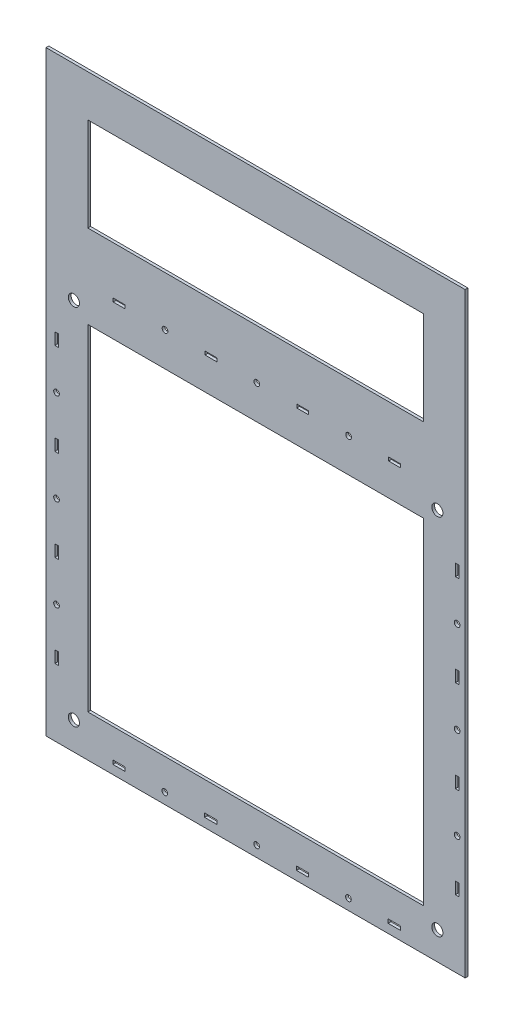
SolidWorks part; units mm, degrees
ref_plane "前视基准面" through (0, 0, 0) normal (0, 0, 1) x (1, 0, 0)
ref_plane "上视基准面" through (0, 0, 0) normal (0, 1, 0) x (1, 0, 0)
ref_plane "右视基准面" through (0, 0, 0) normal (1, 0, 0) x (0, 0, -1)
sketch "草图1" plane through (0, 0, 0) normal (0, 0, 1) x (1, 0, 0)
  line L0 (95.3243, -141.495) -> (104.1243, -141.495)
  line L1 (0.7243, -148.895) -> (0.7243, -142.895) construction
  line L2 (0.7243, -142.895) -> (33.7243, -142.895) construction
  line L3 (33.7243, -142.895) -> (66.7243, -142.895) construction
  line L4 (29.3243, -141.495) -> (38.1243, -141.495)
  line L5 (29.3243, -141.495) -> (29.3243, -144.295)
  line L6 (29.3243, -144.295) -> (38.1243, -144.295)
  line L7 (38.1243, -141.495) -> (38.1243, -144.295)
  line L8 (29.3243, -141.495) -> (38.1243, -144.295) construction
  line L9 (29.3243, -144.295) -> (38.1243, -141.495) construction
  line L10 (66.7243, -142.895) -> (99.7243, -142.895) construction
  line L11 (95.3243, -141.495) -> (95.3243, -144.295)
  line L12 (95.3243, -144.295) -> (104.1243, -144.295)
  line L13 (95.3243, -144.295) -> (104.1243, -141.495) construction
  line L14 (104.1243, -144.295) -> (104.1243, -141.495)
  line L15 (-36.6757, -141.495) -> (-36.6757, -144.295)
  line L16 (-27.8757, -141.495) -> (-36.6757, -141.495)
  line L17 (-27.8757, -141.495) -> (-27.8757, -144.295)
  line L18 (-27.8757, -144.295) -> (-36.6757, -144.295)
  line L19 (-93.8757, -141.495) -> (-93.8757, -144.295)
  line L20 (-102.6757, -144.295) -> (-102.6757, -141.495)
  line L21 (-93.8757, -141.495) -> (-102.6757, -141.495)
  line L22 (-93.8757, -144.295) -> (-102.6757, -144.295)
  line L23 (-141.8757, 95.705) -> (-141.8757, 104.205)
  line L24 (-144.3757, 95.705) -> (-144.3757, 104.205)
  line L25 (-144.3757, 104.205) -> (-141.8757, 104.205)
  line L26 (-141.8757, 95.705) -> (-144.3757, 95.705)
  line L27 (-141.8757, 29.705) -> (-141.8757, 38.205)
  line L28 (-141.8757, 38.205) -> (-144.3757, 38.205)
  line L29 (-144.3757, 29.705) -> (-144.3757, 38.205)
  line L30 (-141.8757, 29.705) -> (-144.3757, 29.705)
  line L31 (-141.8757, -27.795) -> (-144.3757, -27.795)
  line L32 (-141.8757, -27.795) -> (-141.8757, -36.295)
  line L33 (-144.3757, -27.795) -> (-144.3757, -36.295)
  line L34 (-141.8757, -36.295) -> (-144.3757, -36.295)
  line L35 (-141.8757, -93.795) -> (-141.8757, -102.295)
  line L36 (-144.3757, -93.795) -> (-144.3757, -102.295)
  line L37 (-141.8757, -93.795) -> (-144.3757, -93.795)
  line L38 (-144.3757, -102.295) -> (-141.8757, -102.295)
  line L39 (95.6243, 143.705) -> (104.1243, 143.705)
  line L40 (95.6243, 146.205) -> (104.1243, 146.205)
  line L41 (104.1243, 146.205) -> (104.1243, 143.705)
  line L42 (95.6243, 143.705) -> (95.6243, 146.205)
  line L43 (29.6243, 143.705) -> (38.1243, 143.705)
  line L44 (38.1243, 143.705) -> (38.1243, 146.205)
  line L45 (29.6243, 146.205) -> (38.1243, 146.205)
  line L46 (29.6243, 143.705) -> (29.6243, 146.205)
  line L47 (-27.8757, 143.705) -> (-27.8757, 146.205)
  line L48 (-27.8757, 143.705) -> (-36.3757, 143.705)
  line L49 (-27.8757, 146.205) -> (-36.3757, 146.205)
  line L50 (-36.3757, 143.705) -> (-36.3757, 146.205)
  line L51 (-93.8757, 143.705) -> (-102.3757, 143.705)
  line L52 (-93.8757, 146.205) -> (-102.3757, 146.205)
  line L53 (-93.8757, 143.705) -> (-93.8757, 146.205)
  line L54 (-102.3757, 146.205) -> (-102.3757, 143.705)
  line L55 (143.6243, -93.795) -> (143.6243, -102.295)
  line L56 (146.1243, -93.795) -> (146.1243, -102.295)
  line L57 (146.1243, -102.295) -> (143.6243, -102.295)
  line L58 (143.6243, -93.795) -> (146.1243, -93.795)
  line L59 (143.6243, -27.795) -> (143.6243, -36.295)
  line L60 (143.6243, -36.295) -> (146.1243, -36.295)
  line L61 (146.1243, -27.795) -> (146.1243, -36.295)
  line L62 (143.6243, -27.795) -> (146.1243, -27.795)
  line L63 (143.6243, 29.705) -> (146.1243, 29.705)
  line L64 (143.6243, 29.705) -> (143.6243, 38.205)
  line L65 (146.1243, 29.705) -> (146.1243, 38.205)
  line L66 (143.6243, 38.205) -> (146.1243, 38.205)
  line L67 (143.6243, 95.705) -> (143.6243, 104.205)
  line L68 (146.1243, 95.705) -> (146.1243, 104.205)
  line L69 (143.6243, 95.705) -> (146.1243, 95.705)
  line L70 (146.1243, 104.205) -> (143.6243, 104.205)
  line L71 (50.2243, -142.895) -> (50.2243, -127.895) construction
  line L72 (17.2243, -142.895) -> (17.2243, -127.895) construction
  line L73 (120.6507, 120.6507) -> (-120.6507, 120.6507)
  line L74 (150.6507, -150.6507) -> (-150.6507, -150.6507)
  line L75 (99.7243, -142.895) -> (104.1243, -144.295) construction
  line L76 (150.6507, -150.6507) -> (150.6507, 150.6507)
  line L78 (-150.6507, -150.6507) -> (-150.6507, 150.6507)
  line L79 (150.6507, -150.6507) -> (-150.6507, 150.6507) construction
  line L80 (150.6507, 150.6507) -> (-150.6507, -150.6507) construction
  line L81 (-120.6507, -120.6507) -> (-120.6507, 120.6507)
  line L82 (120.6507, -120.6507) -> (-120.6507, -120.6507)
  line L83 (120.6507, -120.6507) -> (120.6507, 120.6507)
  line L84 (-150.6507, 150.6507) -> (-150.6507, 277.9507)
  line L85 (-150.6507, 277.9507) -> (150.6507, 277.9507)
  line L86 (150.6507, 277.9507) -> (150.6507, 150.6507)
  line L87 (150.6507, 150.6507) -> (-150.6507, 150.6507) construction
  line L88 (150.6507, 150.6507) -> (-150.6507, 150.6507) construction
  line L89 (-120.6507, 180.6507) -> (-120.6507, 247.9507)
  line L90 (-120.6507, 247.9507) -> (120.6507, 247.9507)
  line L91 (120.6507, 247.9507) -> (120.6507, 180.6507)
  line L92 (120.6507, 180.6507) -> (-120.6507, 180.6507)
  circle A0 centre (0.7243, -142.895) radius 2.05
  circle A1 centre (66.7243, -142.895) radius 2.05
  circle A2 centre (-65.2757, -142.895) radius 2.05
  circle A3 centre (-143.1257, 66.955) radius 2.05
  circle A4 centre (-143.1257, 0.955) radius 2.05
  circle A5 centre (-143.1257, -65.045) radius 2.05
  circle A6 centre (66.8743, 144.955) radius 2.05
  circle A7 centre (0.8743, 144.955) radius 2.05
  circle A8 centre (-65.1257, 144.955) radius 2.05
  circle A9 centre (144.8743, -65.045) radius 2.05
  circle A10 centre (144.8743, 0.955) radius 2.05
  circle A11 centre (144.8743, 66.955) radius 2.05
  circle A12 centre (-130.6507, -130.6507) radius 4
  circle A18 centre (-130.6507, 130.6507) radius 4
  circle A19 centre (130.6507, 130.6507) radius 4
  circle A20 centre (130.6507, -130.6507) radius 4
  point P25 (0, 0)
  dimension "D4" = 66
  dimension "D5" = 33
  dimension "D6" = 4.1
  dimension "D9" = 20
  dimension "D13" = 8
  dimension "D1" = 8.8
  dimension "D2" = 2.8
  dimension "D3" = 30
  dimension "D7" = 8.8
  dimension "D8" = 2.8
  dimension "D11" = 127.3
  dimension "D10" = 301.3014
  dimension "D14" = 4
  dimension "D12" = 30
extrude "凸台-拉伸1" add sketch "草图1" along normal blind 2
